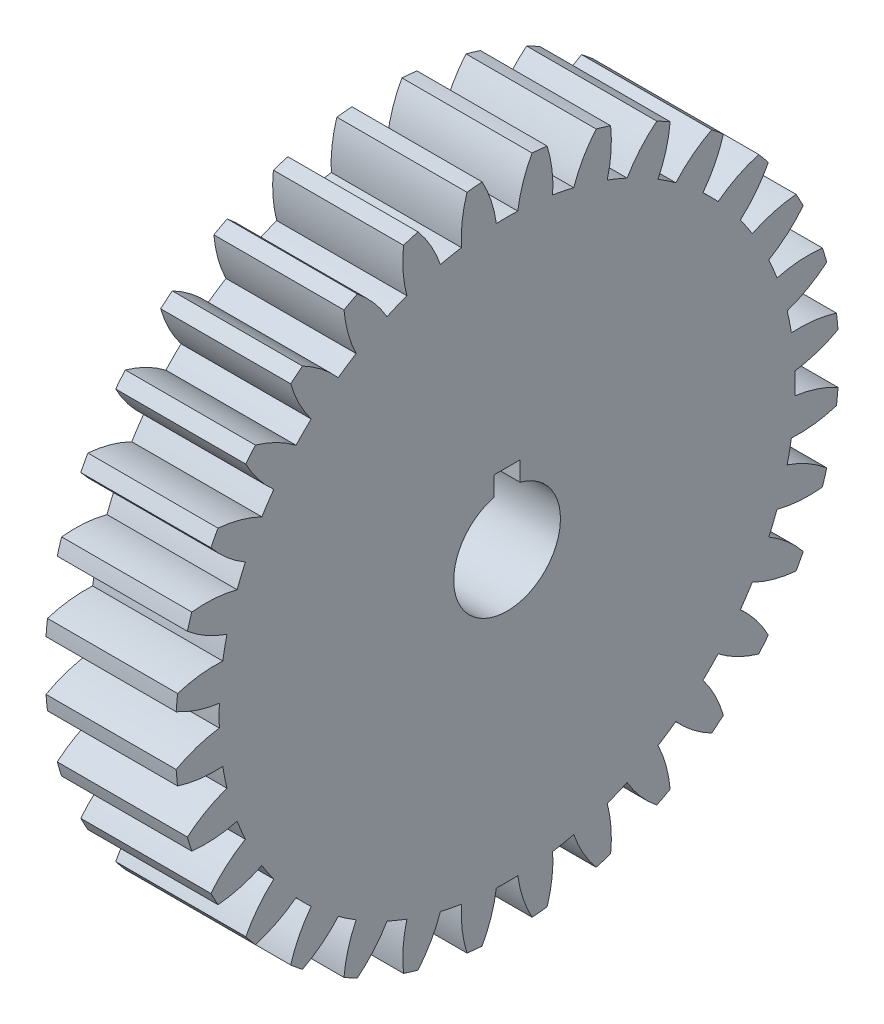
SolidWorks part; units mm, degrees
ref_plane "Plane1" through (0, 0, 0) normal (0, 0, 1) x (1, 0, 0)
ref_plane "Plane2" through (0, 0, 0) normal (0, 1, 0) x (1, 0, 0)
ref_plane "Plane3" through (0, 0, 0) normal (1, 0, 0) x (0, 0, -1)
sketch "HoldingSke" plane through (0, 0, 0) normal (0, 1, 0) x (1, 0, 0)
  line L0 (0, 0) -> (0.5654, -0.3533)
  line L1 (-15, 0) -> (100, 0) construction
  line L2 (0, 0) -> (-2.1039, 2.3779)
  line L3 (0, 0) -> (-11.863, 4.5341)
  line L4 (0, 0) -> (7.3237, 4.5764)
  line L5 (0, 0) -> (-46.8476, -17.4728)
  line L6 (0, 0) -> (-8.2896, -5.593)
  line L7 (-2.1039, 2.3779) -> (8.6586, 51.2059)
  line L8 (-76.2, 54.61) -> (-75.2, 54.61)
  line L9 (-67.7845, 28.3722) -> (-49.3413, 33.142)
  line L10 (-76.2, 71.12) -> (104.1128, 71.12)
  line L11 (0, 0) -> (-10, 0)
  line L12 (-76.2, 101.6) -> (-76.147, 101.6)
  line L13 (24.9733, 27.94) -> (52.9518, 28.4284)
  line L14 (24.9733, 27.94) -> (24.9743, 27.94)
  line L15 (24.9733, 27.94) -> (100.4006, 29.5858)
  line L16 (-63.627, -1.5) -> (-12.827, -1.5)
  circle A0 centre (0, 0) radius 3
  circle A1 centre (0, 0) radius 22.124
  circle A2 centre (0, 0) radius 37.5
  circle A3 centre (0, 0) radius 3
  dimension "MHD" = 44.248
  dimension "Hub_dia" = 75
  dimension "Bore" = 6
  dimension "MBD" = 6
  dimension "Num_teeth" = 32
  dimension "Pitch_radius" = 180.3128
  dimension "Pitch" = 0.6667
  dimension "Width" = 10
  dimension "Overall_len" = 50
  dimension "Show_teeth" = 32
  dimension "Thickness" = 10
  dimension "OAL" = 50.0001
  dimension "T_dim" = 1
  dimension "Ap" = 14.5
  dimension "H" = 19.05
  dimension "Backlash" = 0.053
  dimension "Addendum_fac" = 1
  dimension "Dedendum_fac" = 1.25
  dimension "Clearance_fac" = 0.25
  dimension "Dedendum_add" = 0.001
  dimension "Module" = 1.5
sketch "BasProSke" plane through (0, 0, 0) normal (0, 1, 0) x (1, 0, 0)
  line L0 (-10, 0) -> (60, 0) construction
  line L1 (0, 0) -> (0, 25.5)
  line L2 (0, 0) -> (10, 0)
  line L3 (10, 0) -> (10, 25.5)
  line L4 (10, 25.5) -> (0, 25.5)
  dimension "Diameter" = 51
  dimension "Thickness" = 10
revolve "Base-Revolve" add sketch "BasProSke" angle 360 about L0
sketch "TooCutSke" plane through (0, 0, 0) normal (1, 0, 0) x (0, 0, -1)
  line L1 (0, 0) -> (0, 107) construction
  line L2 (0, 0) -> (-1.2704, 23.9664) construction
  line L3 (0, 0) -> (-4.7, 47.72) construction
  line L4 (-1.2704, 23.9664) -> (-2.35, 23.86) construction
  arc A0 (0.8248, 22.1086) -> (-0.8248, 22.1086) centre (0, 0) ccw
  arc A1 (1.9336, 25.4521) -> (-1.9336, 25.4521) centre (0, 0) ccw
  circle A2 centre (0, 0) radius 24 construction
  circle A3 centre (0, 0) radius 23.2355 construction
  arc A4 (-0.8248, 22.1086) -> (-1.9336, 25.4521) centre (-10.3366, 20.8098) ccw
  arc A5 (1.9336, 25.4521) -> (0.8248, 22.1086) centre (10.3366, 20.8098) ccw
  dimension "Root_dia" = 44.248
  dimension "Overcut_dia" = 51.0508
  dimension "Pitch_dia" = 48
  dimension "Base_dia" = 46.4711
  dimension "Flank_rad" = 9.6
  dimension "Half_ang" = 5.625
  dimension "Half_CT" = 1.0849
extrude "ToothCut" cut sketch "TooCutSke" along normal through all
fillet "Breaks" [suppressed] radius 0.03
fillet "RootFillets" [suppressed] radius 0.376
pattern_circular "TeethCuts" count 32 every 11.25 about axis through (-10, 0, 0) along (1, 0, 0) of "ToothCut", "RootFillets", "Breaks"
sketch "HubNeaOneSke" [suppressed] plane through (0, 0, 0) normal (-1, 0, 0) x (0, 0, 1)
  circle A0 centre (0, 0) radius 12.7
  dimension "Diameter" = 44.248
extrude "HubNearOne" [suppressed] add sketch "HubNeaOneSke" along normal blind 40.0001
sketch "HubNeaBotSke" [suppressed] plane through (0, 0, 0) normal (-1, 0, 0) x (0, 0, 1)
  circle A0 centre (0, 0) radius 12.7
  dimension "Diameter" = 44.248
extrude "HubNearBoth" [suppressed] add sketch "HubNeaBotSke" along normal blind 20
ref_plane "FarPln" through (10, 0, 0) normal (1, 0, 0) x (0, 0, -1)
sketch "HubFarSke" [suppressed] plane through (12.7, 0, 0) normal (1, 0, 0) x (0, 0, -1)
  circle A0 centre (0, 0) radius 12.7
  dimension "Diameter" = 44.248
extrude "HubFar" [suppressed] add sketch "HubFarSke" along normal blind 20
sketch "BorSke" plane through (0, 0, 0) normal (1, 0, 0) x (0, 0, -1)
  circle A0 centre (0, 0) radius 3
  dimension "Diameter" = 6
extrude "Bore" cut sketch "BorSke" along normal mid plane 100.0001
sketch "KeySke" plane through (0, 0, 0) normal (1, 0, 0) x (0, 0, -1)
  line L0 (-1, 0) -> (-1, 4)
  line L1 (-1, 4) -> (1, 4)
  line L2 (1, 4) -> (1, 0)
  line L3 (0, 0) -> (0, 34) construction
  line L4 (-1, 0) -> (1, 0)
  dimension "Offset" = 4
  dimension "Width" = 2
extrude "Keyway" cut sketch "KeySke" along normal mid plane 100.0001
pattern_circular "Keyway2" [suppressed] count 2 every 90 about axis through (-10, 0, 0) along (1, 0, 0)
sketch "Sketch1" plane through (10, 0, 0) normal (1, 0, 0) x (0, 0, -1)
  line L0 (-1, 3.9762) -> (-1, 5.4705)
  line L1 (-1, 4) -> (-1, 2.8284) construction
  line L2 (-1, 5.4705) -> (1, 5.4705)
  line L3 (1, 3.9762) -> (1, 5.4705)
  line L4 (1, 2.8284) -> (1, 4) construction
  arc A0 (-1, 3.9762) -> (1, 3.9762) centre (0, 0) ccw
  dimension "D1" = 8.2
extrude "Cut-Extrude1" cut sketch "Sketch1" against normal through all
equation "' \"Module@HoldingSke\" = 6.35"
equation "' \"Num_teeth@HoldingSke\" = 12"
equation "' \"Ap@HoldingSke\" =  20"
equation "' \"Width@HoldingSke\" = 0.5 * 25.4"
equation "' \"Hub_dia@HoldingSke\"= 1 * 25.4"
equation "' \"Overall_len@HoldingSke\" = 1.0 * 25.4"
equation "' \"Bore@HoldingSke\" = 0.75 * 25.4"
equation "' \"T_dim@HoldingSke\" = 0.1 * 25.4"
equation "' \"Width@KeySke\" = 0.25 * 25.4"
equation "' \"Show_teeth@HoldingSke\" = 13"
equation "' \"Backlash@HoldingSke\" = 0.009 * 25.4"
equation "' \"Addendum_fac@HoldingSke\" = 1.0"
equation "' \"Dedendum_fac@HoldingSke\" = 1.25"
equation "' \"Dedendum_add@HoldingSke\" = 0.00005 * 25.4"
equation "' \"Clearance_fac@HoldingSke\" = 0.25"
equation "\"Pitch@HoldingSke\" = 1 / \"Module@HoldingSke\""
equation "\"Overcut_dia@TooCutSke\" = (\"Num_teeth@HoldingSke\" + 2 * \"Addendum_fac@HoldingSke\") / \"Pitch@HoldingSke\" + 0.002 * 25.4"
equation "\"Pitch_dia@TooCutSke\" = \"Num_teeth@HoldingSke\" / \"Pitch@HoldingSke\""
equation "\"Base_dia@TooCutSke\" = \"Num_teeth@HoldingSke\" / \"Pitch@HoldingSke\" * cos((\"Ap@HoldingSke\"  * 3.14159265 / 180))"
equation "\"Root_dia@TooCutSke\" = (\"Num_teeth@HoldingSke\" + 2) / \"Pitch@HoldingSke\" - 2 * (\"Addendum_fac@HoldingSke\" + \"Dedendum_fac@HoldingSke\") / \"Pitch@HoldingSke\" - \"Dedendum_add@HoldingSke\" * 2"
equation "\"Half_ang@TooCutSke\" = 180 / \"Num_teeth@HoldingSke\""
equation "\"Half_CT@TooCutSke\" = \"Num_teeth@HoldingSke\" / \"Pitch@HoldingSke\" * sin((3.14159265 / 2 / \"Num_teeth@HoldingSke\")) / 2 - 7 * \"Backlash@HoldingSke\" / 4"
equation "\"Flank_rad@TooCutSke\" = \"Num_teeth@HoldingSke\" / \"Pitch@HoldingSke\" / 5"
equation "\"Radius@RootFillets\" = \"Clearance_fac@HoldingSke\" / \"Pitch@HoldingSke\" + \"Dedendum_add@HoldingSke\""
equation "\"Break_rad@Breaks\" = 0.02 / \"Pitch@HoldingSke\""
equation "\"Thickness@HoldingSke\" = \"Width@HoldingSke\""
equation "\"OAL@HoldingSke\" = \"Thickness@HoldingSke\""
equation "\"MHD@HoldingSke\" = (\"Num_teeth@HoldingSke\" + 2) / \"Pitch@HoldingSke\" - 2 * (\"Addendum_fac@HoldingSke\" + \"Dedendum_fac@HoldingSke\")  / \"Pitch@HoldingSke\" - \"Dedendum_add@HoldingSke\" * 2"
equation "\"MBD@HoldingSke\" = (\"Num_teeth@HoldingSke\" + 2) / \"Pitch@HoldingSke\" - 2 * (\"Addendum_fac@HoldingSke\" + \"Dedendum_fac@HoldingSke\")  / \"Pitch@HoldingSke\" - \"Dedendum_add@HoldingSke\" * 2 - 0.002 * 25.4"
equation "\"MHD@HoldingSke\" = ((sgn( \"MHD@HoldingSke\" - \"Hub_dia@HoldingSke\" )-1)*( \"MHD@HoldingSke\" - \"Hub_dia@HoldingSke\" ))/-2+ \"Hub_dia@HoldingSke\""
equation "\"MBD@HoldingSke\" = ((sgn( \"MBD@HoldingSke\" - \"Bore@HoldingSke\" )-1)*( \"MBD@HoldingSke\" - \"Bore@HoldingSke\" ))/-2+ \"Bore@HoldingSke\""
equation "\"OAL@HoldingSke\" = ((sgn( \"OAL@HoldingSke\" - \"Overall_len@HoldingSke\" )+1)*( \"OAL@HoldingSke\" - \"Overall_len@HoldingSke\" ))/2 + \"Overall_len@HoldingSke\" + 0.000002 * 25.4"
equation "\"Num_teeth@TeethCuts\" = int( \"Show_teeth@HoldingSke\" ) + 1"
equation "\"Num_teeth@TeethCuts\" = ((sgn( \"Num_teeth@TeethCuts\" - \"Num_teeth@HoldingSke\" )-1)*( \"Num_teeth@TeethCuts\" - \"Num_teeth@HoldingSke\" ))/-2+ \"Num_teeth@HoldingSke\""
equation "\"Num_teeth@TeethCuts\" = ((sgn( \"Num_teeth@TeethCuts\" - 2.0)+1)*( \"Num_teeth@TeethCuts\" - 2.0))/2 +2.0"
equation "\"Angle@TeethCuts\" = 360.0 / \"Num_teeth@HoldingSke\""
equation "\"Diameter@BasProSke\" = (\"Num_teeth@HoldingSke\" + 2 * \"Addendum_fac@HoldingSke\") / \"Pitch@HoldingSke\""
equation "\"Thickness@BasProSke\"  = \"Thickness@HoldingSke\""
equation "' \"Fillet_rad@BasProSke\" =  \"Thickness@HoldingSke\" * 0.05"
equation "\"MHD@HoldingSke\" = ((sgn( \"MHD@HoldingSke\" - \"Root_dia@TooCutSke\" )-1)*( \"MHD@HoldingSke\" - \"Root_dia@TooCutSke\" ))/-2+ \"Root_dia@TooCutSke\""
equation "\"Diameter@HubNeaOneSke\" = \"MHD@HoldingSke\""
equation "\"Length@HubNearOne\" = \"OAL@HoldingSke\" - \"Thickness@BasProSke\""
equation "\"Diameter@HubNeaBotSke\" = \"MHD@HoldingSke\""
equation "\"Length@HubNearBoth\" = ( \"OAL@HoldingSke\" - \"Thickness@BasProSke\" ) / 2.0"
equation "\"Thickness@FarPln\" = \"Thickness@BasProSke\""
equation "\"Diameter@HubFarSke\" = \"MHD@HoldingSke\""
equation "\"Length@HubFar\" = ( \"OAL@HoldingSke\" - \"Thickness@BasProSke\" ) / 2.0"
equation "\"Diameter@BorSke\" = \"MBD@HoldingSke\""
equation "\"D1@Bore\" = \"OAL@HoldingSke\" * 2.0"
equation "\"D1@Keyway\" = \"OAL@HoldingSke\" * 2.0"
equation "\"Offset@KeySke\" = \"T_dim@HoldingSke\" + \"MBD@HoldingSke\" / 2.0"
